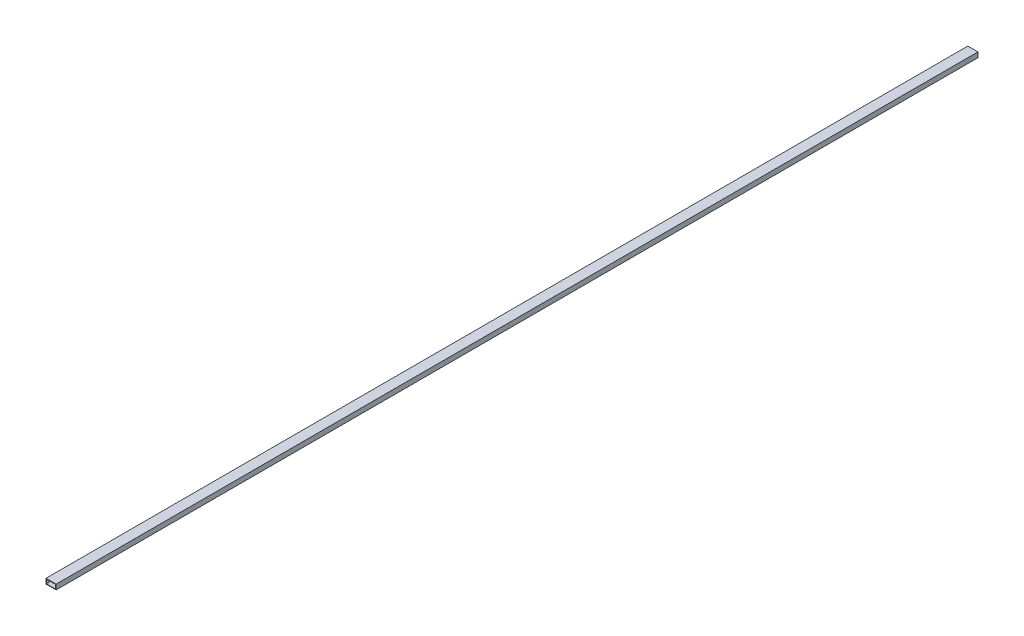
SolidWorks part; units mm, degrees
material "1100-H18 棒材(SS)"
ref_plane "前视基准面" through (0, 0, 0) normal (0, 0, 1) x (1, 0, 0)
ref_plane "上视基准面" through (0, 0, 0) normal (0, 1, 0) x (1, 0, 0)
ref_plane "右视基准面" through (0, 0, 0) normal (1, 0, 0) x (0, 0, -1)
other "Configuration Table"
sketch "草图1" plane through (0, 0, 0) normal (0, 0, 1) x (1, 0, 0)
  line L1 (0, 0) -> (20, 0)
  line L2 (0, 0) -> (0, 10)
  line L3 (0, 10) -> (20, 10)
  line L4 (20, 0) -> (20, 10)
  line L5 (1, 1) -> (19, 1)
  line L6 (1, 1) -> (1, 9)
  line L7 (1, 9) -> (19, 9)
  line L8 (19, 1) -> (19, 9)
  dimension "D1" = 20
  dimension "D2" = 10
  dimension "D3" = 1
  dimension "D4" = 1
  dimension "D5" = 1
  dimension "D6" = 1
extrude "凸台-拉伸1" add sketch "草图1" along normal blind 1820
